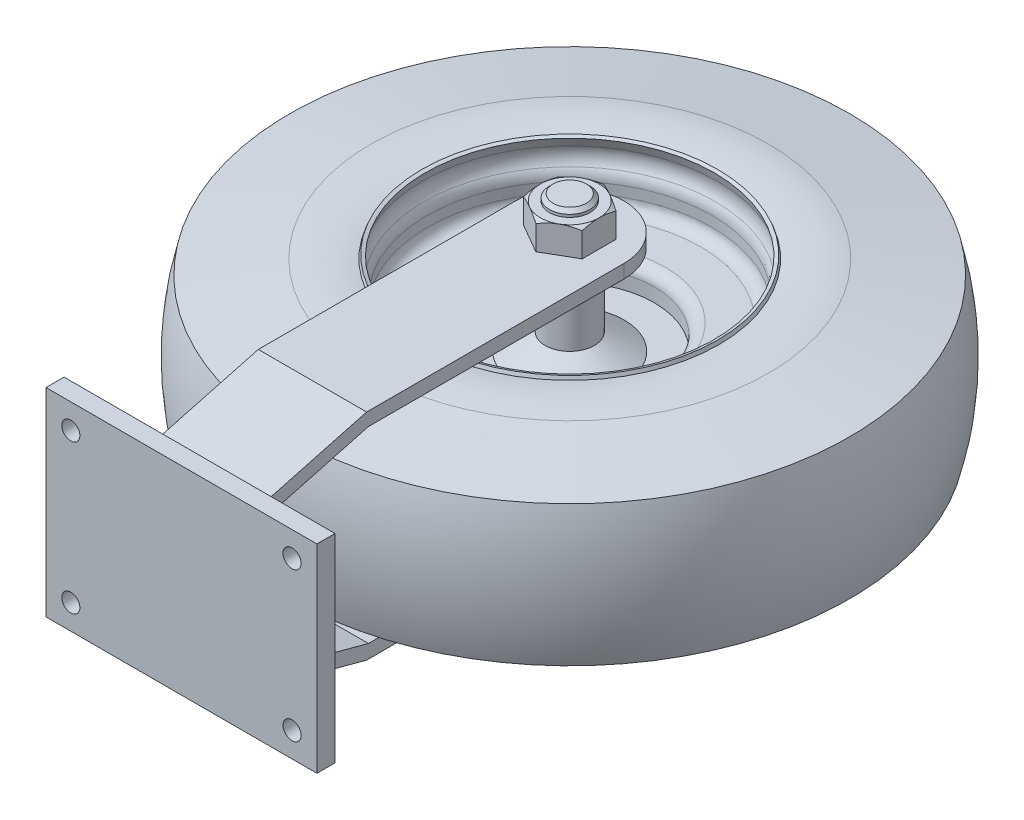
SolidWorks part; units mm, degrees
ref_plane "Front Plane" through (0, 0, 0) normal (0, 0, 1) x (1, 0, 0)
ref_plane "Top Plane" through (0, 0, 0) normal (0, 1, 0) x (1, 0, 0)
ref_plane "Right Plane" through (0, 0, 0) normal (1, 0, 0) x (0, 0, -1)
sketch "Sketch2" plane through (0, 0, 0) normal (0, 0, 1) x (1, 0, 0)
  line L0 (-95.25, -69.85) -> (95.25, 69.85) construction
  line L1 (-95.25, 69.85) -> (95.25, 69.85)
  line L2 (-95.25, 69.85) -> (-95.25, -69.85)
  line L3 (-95.25, -69.85) -> (95.25, -69.85)
  line L4 (95.25, 69.85) -> (95.25, -69.85)
  line L5 (0, 0) -> (0, 69.85) construction
  line L6 (0, 0) -> (95.25, 0) construction
  line L7 (-77.7875, 52.3875) -> (77.7875, 52.3875) construction
  line L8 (77.7875, 52.3875) -> (77.7875, -52.3875) construction
  line L9 (0, 0) -> (77.7875, 0) construction
  line L10 (0, 0) -> (0, 52.3875) construction
  circle A0 centre (-77.7875, 52.3875) radius 6.35
  circle A1 centre (-77.7875, -52.3875) radius 6.35
  circle A2 centre (77.7875, -52.3875) radius 6.35
  circle A3 centre (77.7875, 52.3875) radius 6.35
  dimension "D4" = 155.575
  dimension "D5" = 104.775
  dimension "D3" = 12.7
  dimension "D1" = 190.5
  dimension "D2" = 139.7
extrude "Plate 2" add sketch "Sketch2" against normal blind 12.7 separate body
sketch "Sketch3" plane through (0, 0, 0) normal (0, 1, 0) x (1, 0, 0)
  line L0 (-38.1, 6.35) -> (38.1, 6.35) construction
  line L1 (-38.1, 0) -> (38.1, 0)
  line L2 (-38.1, 0) -> (-38.1, 273.05)
  line L3 (-38.1, 273.05) -> (38.1, 273.05) construction
  line L4 (38.1, 0) -> (38.1, 273.05)
  arc A0 (-38.1, 273.05) -> (38.1, 273.05) centre (0, 273.05) cw
  circle A1 centre (0, 273.05) radius 203.2 construction
  point P9 (0, 69.85)
  point P10 (0, 476.25)
  dimension "Wheel Dia" = 406.4
  dimension "D1" = 6.35
  dimension "D2" = 76.2
  dimension "Mounting Height" = 476.25
extrude "Boss-Extrude3" add sketch "Sketch3" along normal mid plane 151.13
sketch "Sketch4" plane through (38.1, 0, 0) normal (1, 0, 0) x (0, 0, -1)
  line L1 (93.3777, 66.04) -> (311.15, 66.04)
  line L2 (12.7, 44.4225) -> (12.7, -44.4225)
  line L3 (93.3777, -66.04) -> (311.15, -66.04)
  line L4 (311.15, 66.04) -> (311.15, -66.04)
  line L5 (311.15, -75.565) -> (311.15, 75.565) construction
  line L6 (93.3777, 66.04) -> (12.7, 44.4225)
  line L7 (12.7, -44.4225) -> (93.3777, -66.04)
  line L9 (0, 75.565) -> (273.05, 75.565) construction
  line L10 (12.7, 54.2835) -> (92.1237, 75.565)
  line L11 (273.05, -75.565) -> (0, -75.565) construction
  line L12 (92.1237, 75.565) -> (12.7, 75.565)
  line L13 (12.7, 54.2835) -> (12.7, 75.565)
  line L14 (12.7, -75.565) -> (92.1237, -75.565)
  line L15 (12.7, -75.565) -> (12.7, -54.2835)
  line L16 (12.7, -54.2835) -> (92.1237, -75.565)
  line L17 (273.05, -75.565) -> (0, -75.565) construction
  line L18 (0, 75.565) -> (273.05, 75.565) construction
  line L19 (12.7, -69.85) -> (12.7, 69.85) construction
  line L20 (0, 0) -> (12.7, 0) construction
  line L21 (0, -69.85) -> (0, 69.85) construction
  dimension "Leg Thickness" = 9.525
  dimension "D2" = 9.525
  dimension "D1" = 88.8449
  dimension "D3" = 9.525
  dimension "D4" = 15
extrude "Cut-Extrude1" cut sketch "Sketch4" against normal blind 107.95
sketch "Sketch12" plane through (0, 69.85, 0) normal (0, 1, 0) x (1, 0, 0)
  line L0 (95.25, 12.7) -> (38.1, 12.7) construction
  line L1 (-95.25, 0) -> (95.25, 0)
  line L2 (-95.25, 0) -> (-95.25, 12.7)
  line L3 (-95.25, 12.7) -> (95.25, 12.7)
  line L4 (95.25, 0) -> (95.25, 12.7)
extrude "Cut-Extrude4" cut sketch "Sketch12" along normal through all
sketch "Sketch13" plane through (0, -69.85, 0) normal (0, -1, 0) x (1, 0, 0)
  line L1 (95.25, 0) -> (-95.25, 0)
  line L2 (95.25, 0) -> (95.25, -12.7)
  line L3 (95.25, -12.7) -> (-95.25, -12.7)
  line L4 (-95.25, 0) -> (-95.25, -12.7)
extrude "Cut-Extrude5" cut sketch "Sketch13" along normal through all
sketch "Sketch6" plane through (0, 0, 0) normal (0, 1, 0) x (1, 0, 0)
  circle A0 centre (0, 273.05) radius 14.2875
  dimension "D1" = 28.575
extrude "Boss-Extrude5" add sketch "Sketch6" against normal mid plane 198.12
chamfer "Chamfer2" distance 2.54 angle 45 2 edges at (0, -99.06, -258.7625) (0, 99.06, -258.7625)
sketch "Sketch8" plane through (0, 0, 0) normal (1, 0, 0) x (0, 0, -1)
  line L1 (69.85, -60.96) -> (476.25, -60.96) construction
  line L2 (69.85, -60.96) -> (69.85, 60.96) construction
  line L3 (69.85, 60.96) -> (476.25, 60.96) construction
  line L4 (476.25, -60.96) -> (476.25, 60.96) construction
  line L10 (273.05, -60.96) -> (273.05, 60.96) construction
  line L11 (273.05, 0) -> (69.85, 0) construction
  line L12 (273.05, -60.96) -> (255.8415, -60.96)
  line L13 (255.8415, -60.96) -> (255.8415, -15.1019)
  line L14 (255.8415, -15.1019) -> (234.7436, -2.921)
  line L15 (234.7436, -2.921) -> (213.6458, -2.921)
  line L16 (213.6458, -2.921) -> (213.6458, -12.5942)
  line L17 (205.7082, -20.5317) -> (180.8854, -20.5317)
  line L19 (273.05, 60.96) -> (273.05, 120.6344) construction
  line L20 (172.9479, -28.4692) -> (172.9479, -35.724)
  line L21 (171.45, -60.96) -> (169.0632, -61.8287)
  line L22 (169.1388, -54.61) -> (171.45, -60.96)
  line L23 (169.0632, -61.8287) -> (168.1923, -59.436)
  line L24 (133.3535, -59.436) -> (76.2, -49.3583)
  line L25 (169.0632, 61.8287) -> (168.1923, 59.436)
  line L26 (169.1388, 54.61) -> (171.45, 60.96)
  line L27 (171.45, 60.96) -> (169.0632, 61.8287)
  line L28 (172.9479, 28.4692) -> (172.9479, 35.724)
  line L29 (205.7082, 20.5317) -> (180.8854, 20.5317)
  line L30 (213.6458, 2.921) -> (213.6458, 12.5942)
  line L31 (234.7436, 2.921) -> (213.6458, 2.921)
  line L32 (255.8415, 15.1019) -> (234.7436, 2.921)
  line L33 (255.8415, 60.96) -> (255.8415, 15.1019)
  line L34 (133.3535, 59.436) -> (76.2, 49.3583)
  line L35 (255.8415, 60.96) -> (273.05, 60.96)
  line L36 (273.05, -60.96) -> (273.05, 60.96)
  arc A0 (213.6458, -12.5942) -> (205.7082, -20.5317) centre (205.7082, -12.5942) cw
  arc A1 (180.8854, -20.5317) -> (172.9479, -28.4692) centre (180.8854, -28.4692) ccw
  arc A2 (172.9479, -35.724) -> (170.6604, -42.9952) centre (160.2479, -35.724) cw
  arc A3 (170.6604, -42.9952) -> (169.1388, -54.61) centre (181.0729, -50.2663) ccw
  arc A4 (76.2, 49.3583) -> (76.2, -49.3583) centre (264.855, 0) ccw
  arc A5 (168.1923, -59.436) -> (133.3535, -59.436) centre (150.7729, 39.3543) cw
  arc A6 (170.6604, 42.9952) -> (169.1388, 54.61) centre (181.0729, 50.2663) cw
  arc A7 (172.9479, 35.724) -> (170.6604, 42.9952) centre (160.2479, 35.724) ccw
  arc A8 (180.8854, 20.5317) -> (172.9479, 28.4692) centre (180.8854, 28.4692) cw
  arc A9 (213.6458, 12.5942) -> (205.7082, 20.5317) centre (205.7082, 12.5942) ccw
  arc A10 (168.1923, 59.436) -> (133.3535, 59.436) centre (150.7729, -39.3543) ccw
  dimension "D15" = 7.9375
  dimension "D16" = 12.7
  dimension "Wheel Width" = 121.92
  dimension "D3" = 30
  dimension "D4" = 5.842
  dimension "D5" = 20
  dimension "D6" = 203.2
  dimension "D7" = 101.6
  dimension "D8" = 84.3915
  dimension "D9" = 42.1957
  dimension "D10" = 21.0979
  dimension "D11" = 58.039
  dimension "D12" = 9.6732
  dimension "D13" = 7.2549
  dimension "D14" = 6.35
  dimension "D17" = 2.54
  dimension "D18" = 1.524
  dimension "D19" = 10
  dimension "D20" = 6.35
  dimension "D21" = 1.524
  dimension "D23" = 17.2085
  dimension "D22" = 98.7166
ref_plane "Plane1" through (0, -60.96, 0) normal (0, 1, 0) x (-1, 0, 0)
sketch "Sketch9" plane through (0, -75.565, 0) normal (0, 1, 0) x (-1, 0, 0)
  line L1 (0, -249.2199) -> (-20.6375, -261.1349)
  line L2 (-20.6375, -261.1349) -> (-20.6375, -284.9651)
  line L3 (-20.6375, -284.9651) -> (0, -296.8801)
  line L4 (0, -296.8801) -> (20.6375, -284.9651)
  line L5 (20.6375, -284.9651) -> (20.6375, -261.1349)
  line L6 (20.6375, -261.1349) -> (0, -249.2199)
  circle A0 centre (0, -273.05) radius 20.6375 construction
  dimension "D1" = 41.275
extrude "Boss-Extrude7" add sketch "Sketch9" against normal blind 19.05 separate body
sketch "Sketch11" plane through (0, -94.615, 0) normal (0, -1, 0) x (1, 0, 0)
  line L0 (0, -249.2199) -> (20.6375, -261.1349) construction
  line L1 (-20.6375, -284.9651) -> (-20.6375, -261.1349) construction
  line L2 (20.6375, -284.9651) -> (0, -296.8801) construction
  circle A0 centre (0, -273.05) radius 20.6375
extrude "Cut-Extrude3" cut sketch "Sketch11" against normal through all draft 60 flip side to cut
mirror "Mirror5" about plane through (0, 0, 0) normal (0, 1, 0) of bodies 117 109 108
combine bodies "Combine1" operation type add bodies to combine 117 120 108
revolve "Revolve1" add sketch "Sketch8" angle 360 about L36
equation "\"D7@Sketch8\" = \"D6@Sketch8\"*.50"
equation "\"D9@Sketch8\" = \"D8@Sketch8\"/2"
equation "\"D10@Sketch8\" = \"D9@Sketch8\"/2"
equation "\"D12@Sketch8\" = \"D11@Sketch8\"/6"
equation "\"D13@Sketch8\" = \"D12@Sketch8\"*.75"
equation "\"D1@Boss-Extrude5\" = \"Wheel Width@Sketch8\"+3.0"
equation "\"D2@Sketch4\" = \"Leg Thickness@Sketch4\""
equation "\"D1@Boss-Extrude3\" = \"Wheel Width@Sketch8\"+(\"Leg Thickness@Sketch4\"*2)+.4"
equation "\"D1@Sketch4\" = \"D22@Sketch8\"*.9"
equation "\"D3@Sketch4\" = \"D2@Sketch4\""
